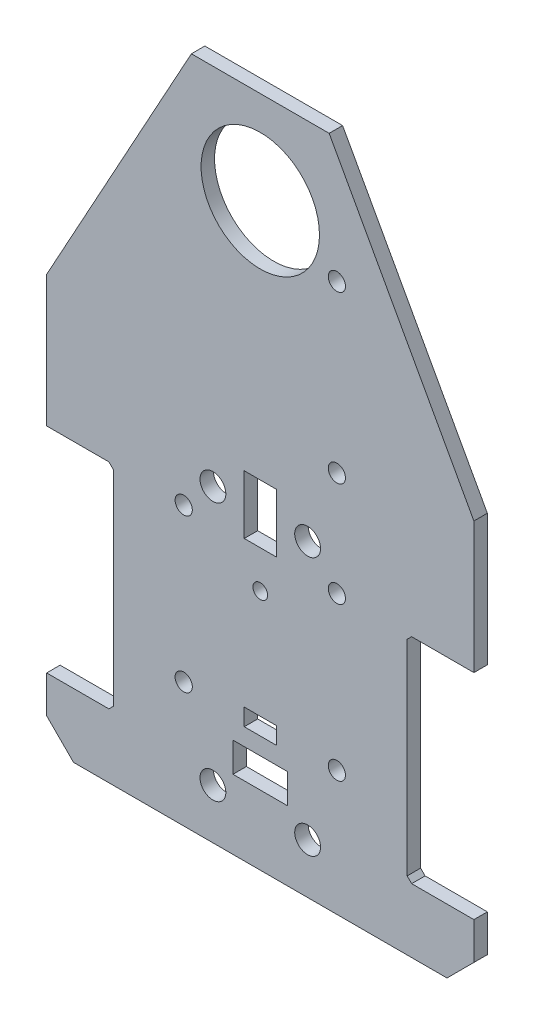
SolidWorks part; units mm, degrees
ref_plane "Plan de face" through (0, 0, 0) normal (0, 0, 1) x (1, 0, 0)
ref_plane "Plan de dessus" through (0, 0, 0) normal (0, 1, 0) x (1, 0, 0)
ref_plane "Plan de droite" through (0, 0, 0) normal (1, 0, 0) x (0, 0, -1)
sketch "Esquisse1" plane through (0, 0, 0) normal (0, 0, 1) x (1, 0, 0)
  line L0 (-15.36, 61.5505) -> (15.36, 61.5505)
  line L1 (15.36, 61.5505) -> (47.64, 2.8105)
  line L2 (47.64, 2.8105) -> (47.64, -26.4695)
  line L3 (47.64, -26.4695) -> (33.76, -26.4695)
  line L4 (32.76, -27.4695) -> (32.76, -73.1695)
  line L5 (33.76, -74.1695) -> (47.64, -74.1695)
  line L6 (47.64, -74.1695) -> (47.64, -82.4495)
  line L7 (41.64, -88.4495) -> (-41.64, -88.4495)
  line L8 (0, 71.403) -> (0, -71.1862) construction
  line L9 (33.76, -26.4695) -> (32.76, -27.4695)
  line L10 (32.76, -73.1695) -> (33.76, -74.1695)
  line L11 (47.64, -82.4495) -> (41.64, -88.4495)
  line L12 (-47.64, -82.4495) -> (-41.64, -88.4495)
  line L13 (-47.64, -74.1695) -> (-47.64, -82.4495)
  line L14 (-33.76, -74.1695) -> (-47.64, -74.1695)
  line L15 (-32.76, -73.1695) -> (-33.76, -74.1695)
  line L16 (-32.76, -27.4695) -> (-32.76, -73.1695)
  line L17 (-33.76, -26.4695) -> (-32.76, -27.4695)
  line L18 (-47.64, -26.4695) -> (-33.76, -26.4695)
  line L19 (-47.64, 2.8105) -> (-47.64, -26.4695)
  line L20 (-15.36, 61.5505) -> (-47.64, 2.8105)
  line L21 (3.576, -58.7255) -> (3.576, -62.5295)
  line L24 (3.576, -62.5295) -> (-3.576, -62.5295)
  line L26 (3.576, -58.7255) -> (-3.576, -58.7255)
  line L27 (-3.575, -13.0895) -> (3.575, -13.0895)
  line L28 (3.575, -13.0895) -> (3.575, -26.1695)
  line L30 (-3.576, -58.7255) -> (-3.576, -62.5295)
  line L31 (-3.575, -13.0895) -> (-3.575, -26.1695)
  line L32 (-6.09, -66.3695) -> (6.09, -66.3695)
  line L33 (6.09, -66.3695) -> (6.09, -72.9695)
  line L34 (6.09, -72.9695) -> (-6.09, -72.9695)
  line L35 (-6.09, -66.3695) -> (-6.09, -72.9695)
  line L36 (-17.076, -60.6215) -> (17.076, -60.6215)
  line L37 (-3.575, -19.6295) -> (17.076, -19.6295) construction
  line L38 (-3.575, -26.1695) -> (3.575, -26.1695)
  line L39 (17.076, -19.6295) -> (-15.36, -19.6295) construction
  circle A0 centre (0, 40.8505) radius 13.2
  circle A4 centre (17.076, -26.4695) radius 1.92
  circle A5 centre (17.076, -60.6215) radius 1.92
  circle A6 centre (10.56, -77.3015) radius 2.88
  circle A7 centre (-10.56, -77.3015) radius 2.88
  circle A8 centre (-17.076, -60.6215) radius 1.92
  circle A9 centre (-17.076, -26.4695) radius 1.92
  circle A11 centre (17.076, 33.8025) radius 1.92
  circle A12 centre (17.076, -3.2012) radius 1.92
  circle A13 centre (0, -34.5471) radius 1.6336
  circle A14 centre (10.56, -19.6269) radius 2.88
  circle A15 centre (-10.56, -19.6269) radius 2.88
  point P7 (32.76, -26.4695)
  point P8 (32.76, -74.1695)
  point P15 (47.64, -88.4495)
  point P21 (0, -88.4495)
  point P30 (0, 61.5505)
  point P61 (0, -62.5295)
  point P62 (0, -58.7255)
  point P63 (0, -21.2693)
  point P64 (0, -13.0895)
  point P69 (0, -72.9695)
  point P70 (0, -66.3695)
  dimension "D13" = 3.84
  dimension "D14" = 3.84
  dimension "D15" = 21.12
  dimension "D18" = 3.84
  dimension "D19" = 3.84
  dimension "D20" = 5.76
  dimension "D33" = 26.4
  dimension "D1" = 15.36
  dimension "D2" = 20.7
  dimension "D3" = 58.74
  dimension "D4" = 29.28
  dimension "D5" = 14.28
  dimension "D6" = 150
  dimension "D7" = 95.28
  dimension "D11" = 95.28
  dimension "D12" = 65.52
  dimension "D17" = 13.08
  dimension "D21" = 34.152
  dimension "D22" = 34.152
  dimension "D23" = 21.12
  dimension "D24" = 7.15
  dimension "D25" = 7.152
  dimension "D26" = 3.804
  dimension "D27" = 12.18
  dimension "D28" = 6.6
  dimension "D29" = 16.68
  dimension "D30" = 11.148
  dimension "D31" = 15.48
  dimension "D32" = 3.84
  dimension "D34" = 53.94
extrude "Boss.-Extru.1" add sketch "Esquisse1" along normal blind 3
